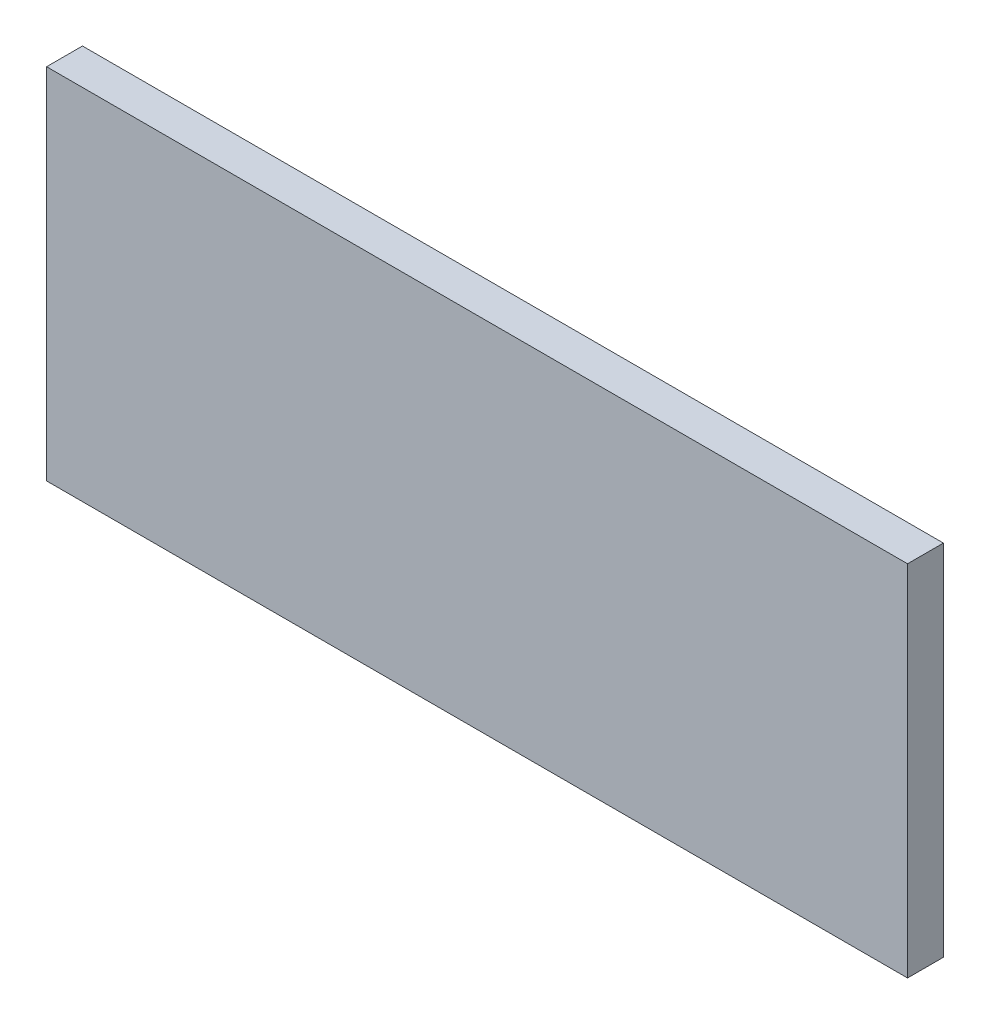
SolidWorks part; units mm, degrees
ref_plane "正面" through (0, 0, 0) normal (0, 0, 1) x (1, 0, 0)
ref_plane "平面" through (0, 0, 0) normal (0, 1, 0) x (1, 0, 0)
ref_plane "右側面" through (0, 0, 0) normal (1, 0, 0) x (0, 0, -1)
sketch "ｽｹｯﾁ1" plane through (0, 0, 0) normal (0, 0, 1) x (1, 0, 0)
  line L1 (-60, -25) -> (60, -25)
  line L2 (-60, -25) -> (-60, 25)
  line L3 (-60, 25) -> (60, 25)
  line L4 (60, -25) -> (60, 25)
  line L5 (-60, -25) -> (60, 25) construction
  line L6 (-60, 25) -> (60, -25) construction
  point P0 (0, 0)
  dimension "D1" = 50
  dimension "D2" = 120
extrude "ﾎﾞｽ - 押し出し1" add sketch "ｽｹｯﾁ1" along normal blind 5
